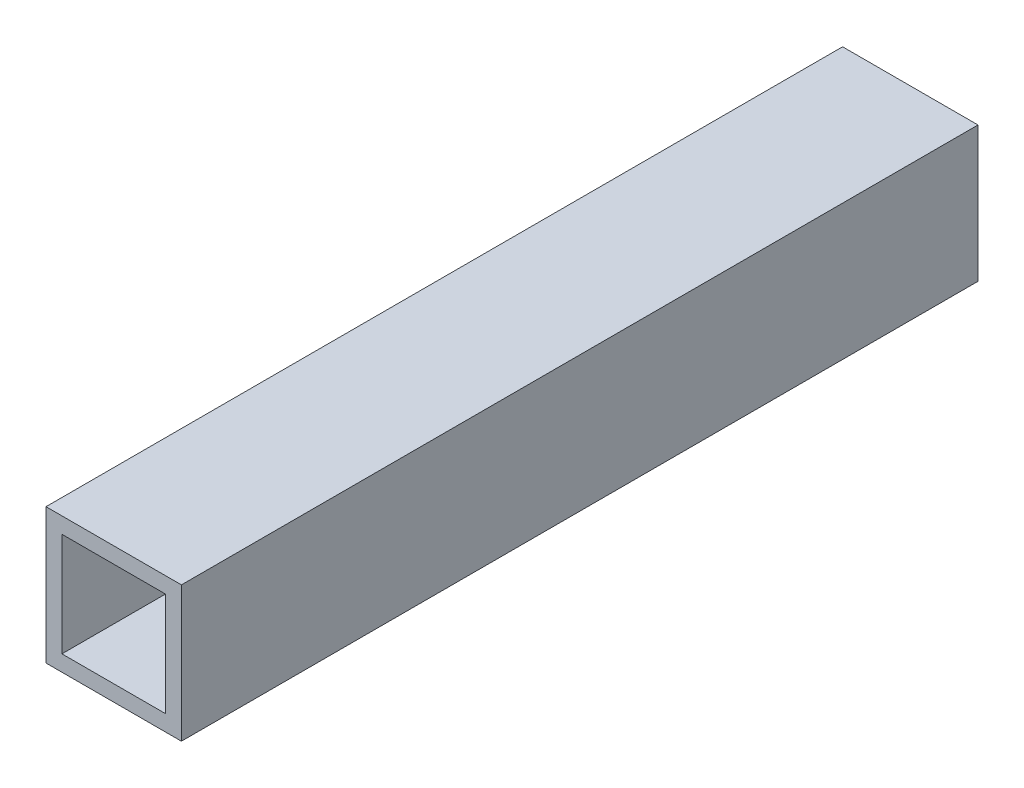
SolidWorks part; units mm, degrees
ref_plane "Front Plane" through (0, 0, 0) normal (0, 0, 1) x (1, 0, 0)
ref_plane "Top Plane" through (0, 0, 0) normal (0, 1, 0) x (1, 0, 0)
ref_plane "Right Plane" through (0, 0, 0) normal (1, 0, 0) x (0, 0, -1)
sketch "Sketch1" plane through (0, 0, 0) normal (0, 0, 1) x (1, 0, 0)
  line L0 (-6.5, -6.5) -> (-6.5, 6.5)
  line L1 (-8.5, -8.5) -> (8.5, -8.5)
  line L2 (-8.5, -8.5) -> (-8.5, 8.5)
  line L3 (-8.5, 8.5) -> (8.5, 8.5)
  line L4 (8.5, -8.5) -> (8.5, 8.5)
  line L5 (-8.5, -8.5) -> (8.5, 8.5) construction
  line L6 (-8.5, 8.5) -> (8.5, -8.5) construction
  line L7 (-6.5, 6.5) -> (6.5, 6.5)
  line L8 (6.5, -6.5) -> (6.5, 6.5)
  line L9 (-6.5, -6.5) -> (6.5, -6.5)
  point P0 (0, 0)
  dimension "D1" = 17
  dimension "D2" = 17
  dimension "D3" = 2
extrude "Boss-Extrude1" add sketch "Sketch1" along normal blind 100
